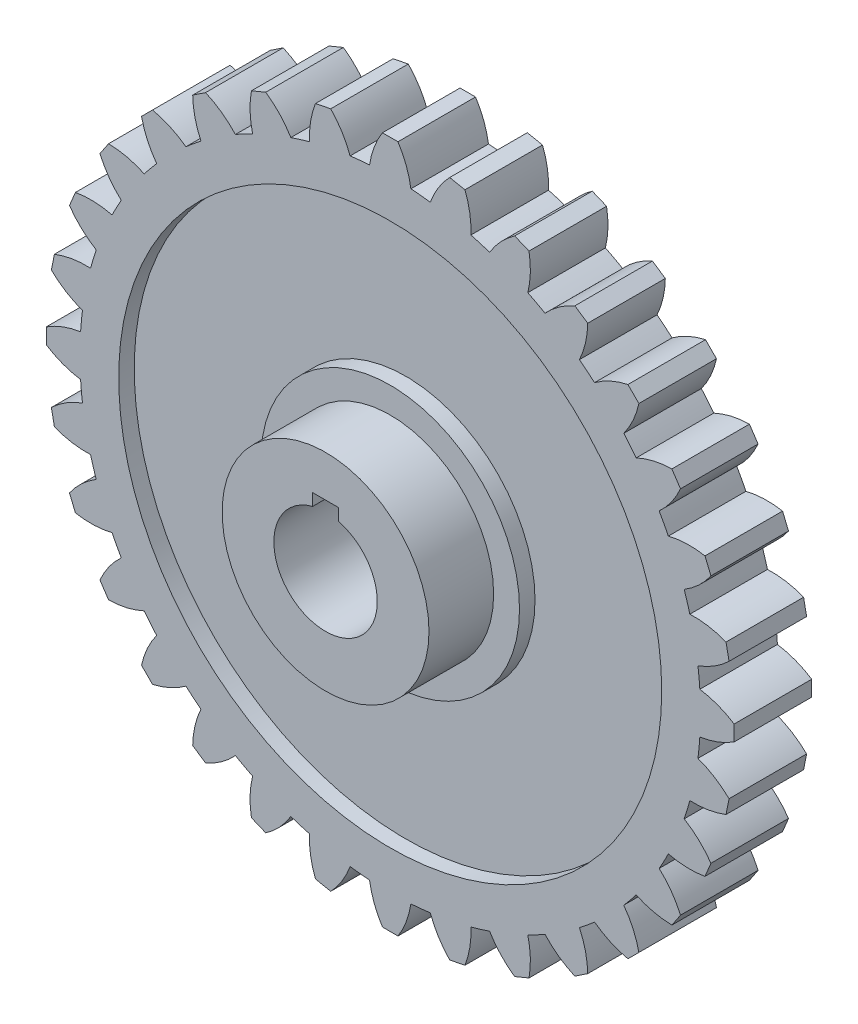
SolidWorks part; units mm, degrees
ref_plane "Front Plane" through (0, 0, 0) normal (0, 0, 1) x (1, 0, 0)
ref_plane "Top Plane" through (0, 0, 0) normal (0, 1, 0) x (1, 0, 0)
ref_plane "Right Plane" through (0, 0, 0) normal (1, 0, 0) x (0, 0, -1)
sketch "Sketch2" plane through (0, 0, 0) normal (0, 0, 1) x (1, 0, 0)
  circle A0 centre (0, 0) radius 60
  dimension "D1" = 120
extrude "Boss-Extrude1" add sketch "Sketch2" along normal mid plane 15
sketch "Sketch3" plane through (0, 0, 7.5) normal (0, 0, 1) x (1, 0, 0)
  line L0 (0, 0) -> (0, 66.5) construction
  line L1 (-1.5, 66.5) -> (1.5, 66.5)
  circle A0 centre (0, 0) radius 60 construction
  arc A1 (4, 59.8665) -> (-4, 59.8665) centre (0, 0) ccw
  arc A2 (1.5, 66.5) -> (4, 59.8665) centre (-12.8082, 57.3198) cw
  arc A3 (-1.5, 66.5) -> (-4, 59.8665) centre (12.8082, 57.3198) ccw
  point P7 (0, 66.5)
  dimension "D3" = 17
  dimension "D1" = 6.5
  dimension "D2" = 3
  dimension "D4" = 8
extrude "Boss-Extrude3" add sketch "Sketch3" along normal up to surface (15 mm away) contours A1 A3 L1 A2
pattern_circular "CirPattern1" count 32 over 360 about axis through (0, 0, 0) along (0, 0, 1) of "Boss-Extrude3"
sketch "Sketch4" plane through (0, 0, 0) normal (0, 0, 1) x (1, 0, 0)
  circle A0 centre (0, 0) radius 20
  dimension "D1" = 40
extrude "Boss-Extrude4" add sketch "Sketch4" along normal mid plane 40
sketch "Sketch5" plane through (0, 0, 20) normal (0, 0, 1) x (1, 0, 0)
  line L1 (-2.5, 12) -> (2.5, 12)
  line L2 (-2.5, 12) -> (-2.5, 9.6825)
  line L3 (2.5, 12) -> (2.5, 9.6825)
  arc A0 (-2.5, 9.6825) -> (2.5, 9.6825) centre (0, 0) ccw
  point P7 (0, 12)
  dimension "D1" = 20
  dimension "D3" = 5
extrude "Cut-Extrude1" cut sketch "Sketch5" against normal through all
sketch "Sketch6" plane through (0, 0, 0) normal (0, 0, 1) x (1, 0, 0)
  circle A2 centre (0, 0) radius 25
  circle A3 centre (0, 0) radius 52.5
  circle A4 centre (0, 0) radius 20 construction
  dimension "D2" = 105
  dimension "D1" = 50
extrude "Cut-Extrude2" cut sketch "Sketch6" against normal blind 3 from surface at 7.5 starting at face at (20, 0, 7.5)
mirror "Mirror1" about plane through (0, 0, 0) normal (0, 0, 1) of "Cut-Extrude2"
